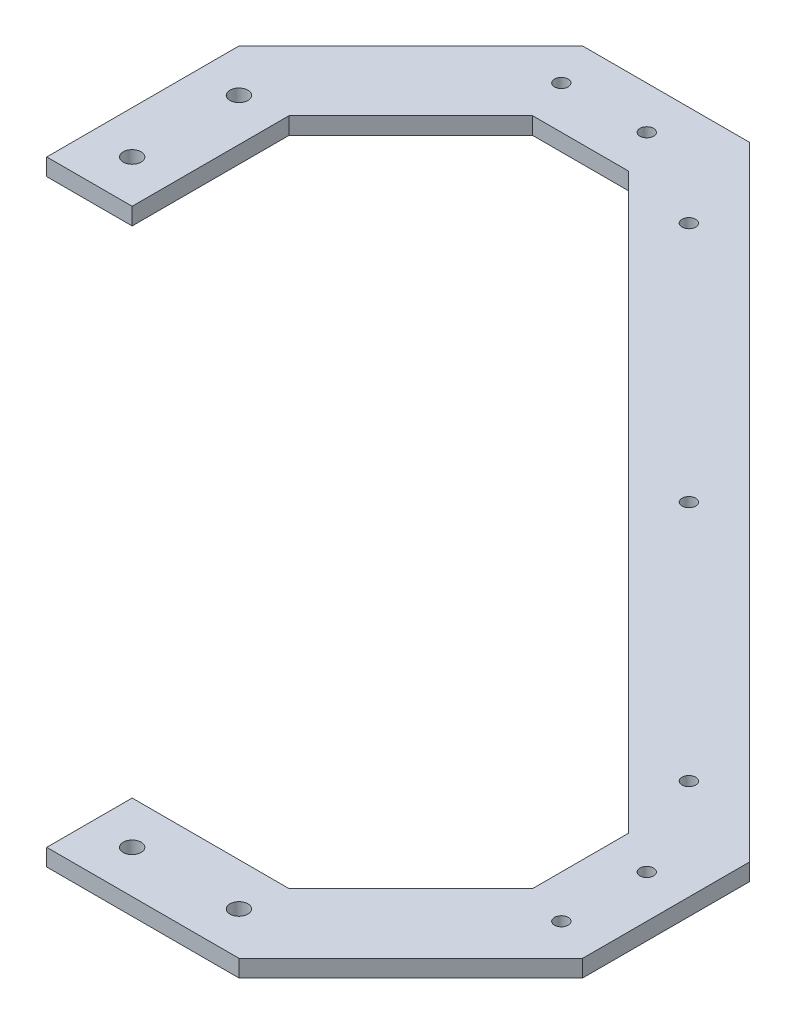
SolidWorks part; units mm, degrees
ref_plane "前视基准面" through (0, 0, 0) normal (0, 0, 1) x (1, 0, 0)
ref_plane "上视基准面" through (0, 0, 0) normal (0, 1, 0) x (1, 0, 0)
ref_plane "右视基准面" through (0, 0, 0) normal (1, 0, 0) x (0, 0, -1)
sketch "草图1" plane through (0, 0, 0) normal (0, 1, 0) x (1, 0, 0)
  line L0 (0, 22.5) -> (20, 22.5) construction
  line L2 (20, 0) -> (0, 0)
  line L3 (0, 0) -> (0, 45)
  line L4 (0, 45) -> (40.25, 85.25)
  line L8 (48.5343, 65.25) -> (20, 36.7157)
  line L10 (10, 22.5) -> (10, 0) construction
  line L12 (0, 0) -> (0, -140) construction
  line L13 (138.1079, -1.8921) -> (152.25, 12.25) construction
  line L14 (48.5343, 65.25) -> (70.9657, 65.25)
  line L22 (0, -140) -> (138.1079, -1.8921) construction
  line L27 (20, 36.7157) -> (20, 0)
  line L32 (59.75, 85.25) -> (59.75, 65.25) construction
  line L33 (59.75, 75.25) -> (30.25, 75.25) construction
  line L34 (20, -455) -> (20, 45) construction
  line L35 (40.25, 85.25) -> (0, 45) construction
  line L36 (40.25, 85.25) -> (79.25, 85.25)
  line L37 (79.25, 85.25) -> (225.25, -60.75)
  line L39 (215.25, -80.25) -> (215.25, -109.75) construction
  line L40 (225.25, -80.25) -> (205.25, -80.25) construction
  line L41 (162.5, -130) -> (140, -130) construction
  line L42 (70.9657, 65.25) -> (205.25, -69.0343)
  line L43 (162.5, -140) -> (162.5, -120) construction
  line L46 (225.25, -99.75) -> (225.25, -60.75)
  line L47 (176.7157, -120) -> (140, -120)
  line L48 (205.25, -91.4657) -> (205.25, -69.0343)
  line L49 (205.25, -91.4657) -> (176.7157, -120)
  line L50 (185, -140) -> (225.25, -99.75)
  line L51 (140, -140) -> (185, -140)
  line L52 (140, -120) -> (140, -140)
  circle A0 centre (10, 10) radius 2.1
  circle A1 centre (10, 35) radius 2.1
  circle A2 centre (175, -130) radius 2.1
  circle A3 centre (150, -130) radius 2.1
  dimension "D4" = 4.2
  dimension "D5" = 25
  dimension "D6" = 45
  dimension "D12" = 140
  dimension "D13" = 45
  dimension "D1" = 10
  dimension "D2" = 20
  dimension "D3" = 45
  dimension "D7" = 20
  dimension "D9" = 20
  dimension "D10" = 20
  dimension "D11" = 195.314
  dimension "D14" = 65.25
extrude "凸台-拉伸1" add sketch "草图1" along normal blind 4
sketch "草图2" plane through (0, 4, 0) normal (0, 1, 0) x (1, 0, 0)
  line L0 (225.25, -99.75) -> (196.9657, -99.75) construction
  line L1 (205.25, -91.4657) -> (176.7157, -120) construction
  line L2 (225.25, -94.75) -> (205.25, -94.75) construction
  line L3 (225.25, -99.75) -> (225.25, -60.75) construction
  line L4 (205.25, -69.0343) -> (205.25, -91.4657) construction
  line L5 (215.25, -94.75) -> (215.25, -74.75) construction
  line L6 (152.25, 12.25) -> (138.1079, -1.8921) construction
  line L7 (225.25, -60.75) -> (79.25, 85.25) construction
  line L8 (70.9657, 65.25) -> (205.25, -69.0343) construction
  line L9 (145.1789, 5.1789) -> (201.7475, -51.3896) construction
  line L10 (45.25, 75.25) -> (65.25, 75.25) construction
  line L11 (45.25, 85.25) -> (45.25, 65.25) construction
  line L12 (40.25, 85.25) -> (40.25, 56.9657) construction
  circle A0 centre (215.25, -94.75) radius 1.6
  circle A1 centre (215.25, -74.75) radius 1.6
  circle A2 centre (201.7475, -51.3896) radius 1.6
  circle A3 centre (145.1789, 5.1789) radius 1.6
  circle A4 centre (88.6104, 61.7475) radius 1.6
  circle A5 centre (65.25, 75.25) radius 1.6
  circle A6 centre (45.25, 75.25) radius 1.6
  dimension "D3" = 3.2
  dimension "D1" = 5
  dimension "D2" = 20
  dimension "D4" = 80
extrude "切除-拉伸1" cut sketch "草图2" against normal blind 50
